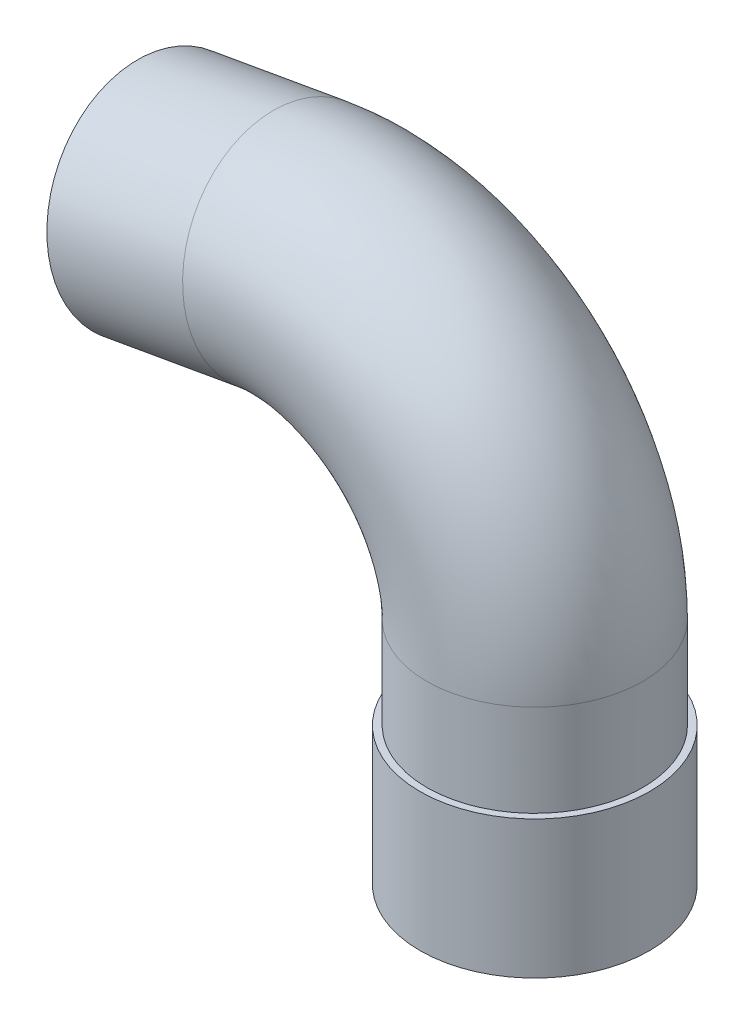
SolidWorks part; units mm, degrees
ref_plane "前视基准面" through (0, 0, 0) normal (0, 0, 1) x (1, 0, 0)
ref_plane "上视基准面" through (0, 0, 0) normal (0, 1, 0) x (1, 0, 0)
ref_plane "右视基准面" through (0, 0, 0) normal (1, 0, 0) x (0, 0, -1)
sketch "草图1" plane through (0, 0, 0) normal (0, 1, 0) x (1, 0, 0)
  circle A0 centre (0, 0) radius 22
  circle A1 centre (0, 0) radius 23.5
  dimension "D1" = 44
  dimension "D2" = 47
sketch "草图2" plane through (0, 0, 0) normal (0, 0, 1) x (1, 0, 0)
  line L0 (0, 0) -> (0, 30)
  line L3 (-52.8142, 74.3163) -> (-82.3584, 69.1069)
  arc A0 (-52.8142, 74.3163) -> (0, 30) centre (-45, 30) cw
  dimension "D2" = 80
  dimension "D3" = 45
  dimension "D5" = 30
  dimension "D1" = 30
sweep "扫描1" add profiles "草图1" path "草图2"
sketch "草图3" plane through (0, 0, 58.7657) normal (0, -1, 0) x (1, 0, 0)
  circle A0 centre (0, -58.7657) radius 23
  circle A1 centre (0, -58.7657) radius 25
  circle A3 centre (0, -58.7657) radius 22 construction
  dimension "D1" = 46
  dimension "D2" = 50
extrude "凸台-拉伸1" add sketch "草图3" along normal blind 20 and the other way blind 10 separate body
